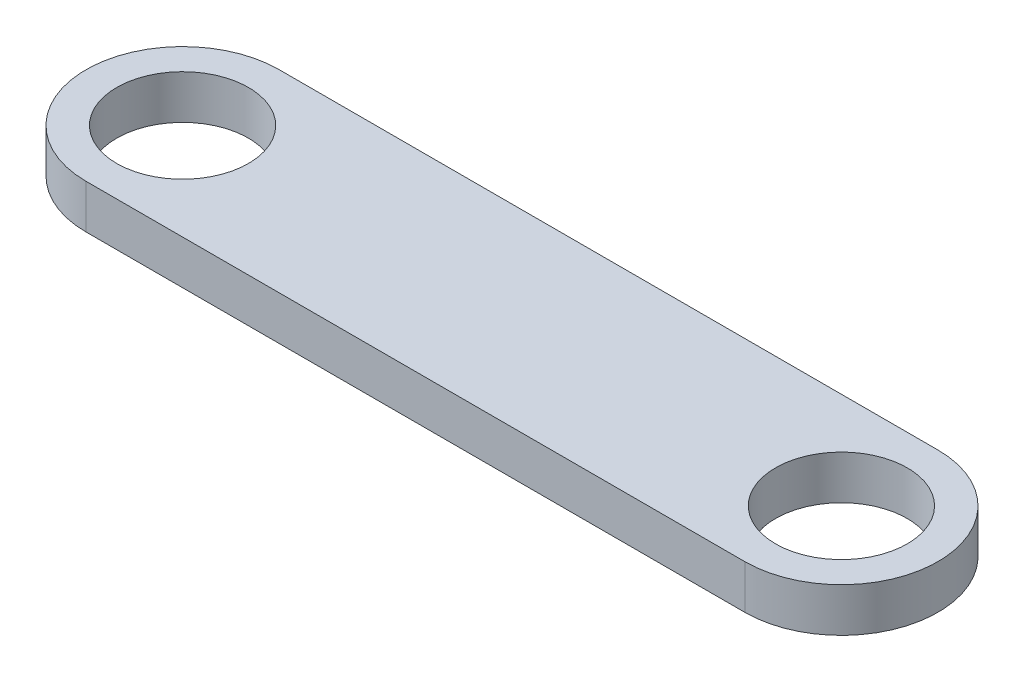
SolidWorks part; units mm, degrees
ref_plane "Plan de face" through (0, 0, 0) normal (0, 0, 1) x (1, 0, 0)
ref_plane "Plan de dessus" through (0, 0, 0) normal (0, 1, 0) x (1, 0, 0)
ref_plane "Plan de droite" through (0, 0, 0) normal (1, 0, 0) x (0, 0, -1)
sketch "Esquisse1" plane through (0, 0, 0) normal (0, 1, 0) x (1, 0, 0)
  line L0 (-14.0585, 0) -> (13.9512, 0) construction
  line L1 (0, 7.4585) -> (0, -6.6) construction
  line L2 (-7.5, 0) -> (7.5, 0) construction
  line L3 (-7.5, 2.2) -> (7.5, 2.2)
  line L4 (-7.5, -2.2) -> (7.5, -2.2)
  arc A0 (-7.5, 2.2) -> (-7.5, -2.2) centre (-7.5, 0) ccw
  arc A1 (7.5, -2.2) -> (7.5, 2.2) centre (7.5, 0) ccw
  circle A2 centre (-7.5, 0) radius 1.5
  circle A3 centre (7.5, 0) radius 1.5
  point P7 (0, 0)
  dimension "D3" = 3
  dimension "D4" = 3
  dimension "D1" = 4.4
  dimension "D2" = 15
extrude "Boss.-Extru.1" add sketch "Esquisse1" along normal blind 1
